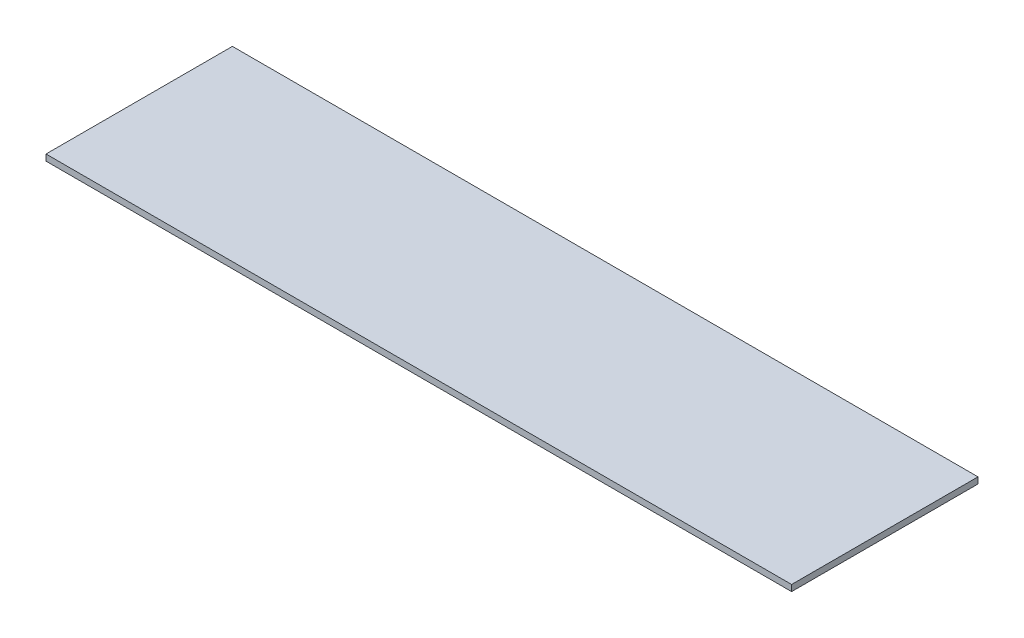
SolidWorks part; units mm, degrees
ref_plane "Front Plane" through (0, 0, 0) normal (0, 0, 1) x (1, 0, 0)
ref_plane "Top Plane" through (0, 0, 0) normal (0, 1, 0) x (1, 0, 0)
ref_plane "Right Plane" through (0, 0, 0) normal (1, 0, 0) x (0, 0, -1)
sketch "Sketch1" plane through (0, 0, 0) normal (0, 1, 0) x (1, 0, 0)
  line L1 (300, -75) -> (-300, -75)
  line L2 (300, -75) -> (300, 75)
  line L3 (300, 75) -> (-300, 75)
  line L4 (-300, -75) -> (-300, 75)
  line L5 (300, -75) -> (-300, 75) construction
  line L6 (300, 75) -> (-300, -75) construction
  point P0 (0, 0)
  dimension "D1" = 150
  dimension "D2" = 600
extrude "Boss-Extrude1" add sketch "Sketch1" along normal blind 5
